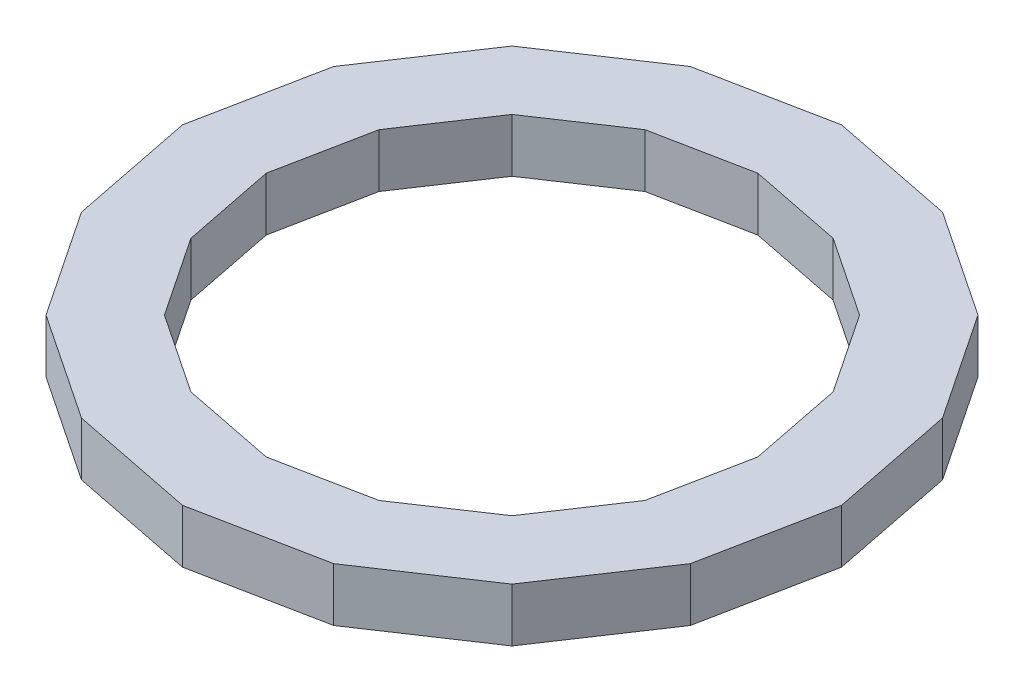
SolidWorks part; units mm, degrees
ref_plane "Front Plane" through (0, 0, 0) normal (0, 0, 1) x (1, 0, 0)
ref_plane "Top Plane" through (0, 0, 0) normal (0, 1, 0) x (1, 0, 0)
ref_plane "Right Plane" through (0, 0, 0) normal (1, 0, 0) x (0, 0, -1)
sketch "Sketch1" plane through (0, 0, 0) normal (0, 1, 0) x (1, 0, 0)
  line L1 (87.3942, 0) -> (80.7417, 33.4443)
  line L2 (80.7417, 33.4443) -> (61.7971, 61.7971)
  line L3 (61.7971, 61.7971) -> (33.4443, 80.7417)
  line L4 (33.4443, 80.7417) -> (0, 87.3942)
  line L5 (0, 87.3942) -> (-33.4443, 80.7417)
  line L6 (-33.4443, 80.7417) -> (-61.7971, 61.7971)
  line L7 (-61.7971, 61.7971) -> (-80.7417, 33.4443)
  line L8 (-80.7417, 33.4443) -> (-87.3942, 0)
  line L9 (-87.3942, 0) -> (-80.7417, -33.4443)
  line L10 (-80.7417, -33.4443) -> (-61.7971, -61.7971)
  line L11 (-61.7971, -61.7971) -> (-33.4443, -80.7417)
  line L12 (-33.4443, -80.7417) -> (0, -87.3942)
  line L13 (0, -87.3942) -> (33.4443, -80.7417)
  line L14 (33.4443, -80.7417) -> (61.7971, -61.7971)
  line L15 (61.7971, -61.7971) -> (80.7417, -33.4443)
  line L16 (80.7417, -33.4443) -> (87.3942, 0)
  line L17 (117.1765, 0) -> (108.257, 44.8415)
  line L18 (108.257, 44.8415) -> (82.8563, 82.8563)
  line L19 (82.8563, 82.8563) -> (44.8415, 108.257)
  line L20 (44.8415, 108.257) -> (0, 117.1765)
  line L21 (0, 117.1765) -> (-44.8415, 108.257)
  line L22 (-44.8415, 108.257) -> (-82.8563, 82.8563)
  line L23 (-82.8563, 82.8563) -> (-108.257, 44.8415)
  line L24 (-108.257, 44.8415) -> (-117.1765, 0)
  line L25 (-117.1765, 0) -> (-108.257, -44.8415)
  line L26 (-108.257, -44.8415) -> (-82.8563, -82.8563)
  line L27 (-82.8563, -82.8563) -> (-44.8415, -108.257)
  line L28 (-44.8415, -108.257) -> (0, -117.1765)
  line L29 (0, -117.1765) -> (44.8415, -108.257)
  line L30 (44.8415, -108.257) -> (82.8563, -82.8563)
  line L31 (82.8563, -82.8563) -> (108.257, -44.8415)
  line L32 (108.257, -44.8415) -> (117.1765, 0)
  circle A1 centre (0, 0) radius 85.715 construction
  circle A2 centre (0, 0) radius 114.925 construction
  dimension "D1" = 29.21
  dimension "D2" = 45.72
extrude "Boss-Extrude1" add sketch "Sketch1" along normal blind 19.05
